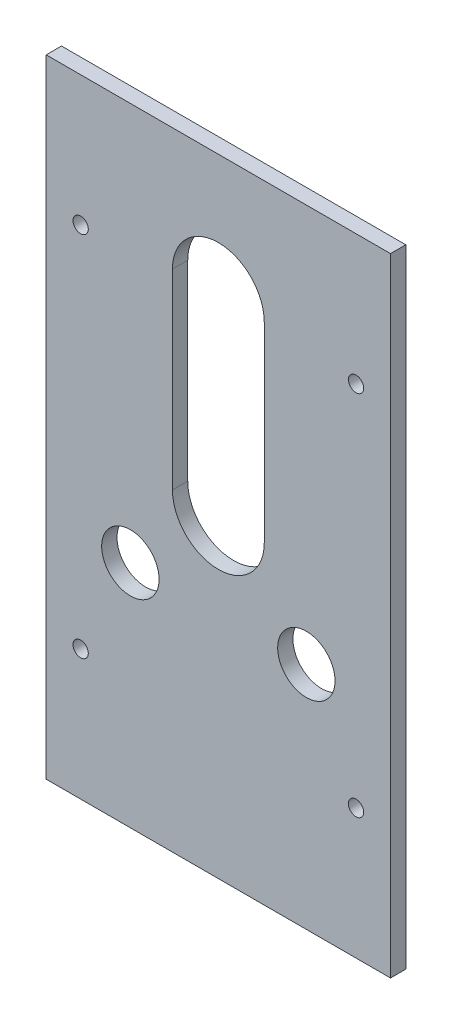
SolidWorks part; units mm, degrees
ref_plane "前视基准面" through (0, 0, 0) normal (0, 0, 1) x (1, 0, 0)
ref_plane "上视基准面" through (0, 0, 0) normal (0, 1, 0) x (1, 0, 0)
ref_plane "右视基准面" through (0, 0, 0) normal (1, 0, 0) x (0, 0, -1)
sketch "草图1" plane through (0, 0, 0) normal (0, 0, 1) x (1, 0, 0)
  line L0 (0, 0) -> (0, 89.6329) construction
  line L1 (-45, -82) -> (45, -82)
  line L2 (-45, -82) -> (-45, 82)
  line L3 (-45, 82) -> (45, 82)
  line L4 (45, -82) -> (45, 82)
  line L5 (-45, -82) -> (45, 82) construction
  line L6 (-45, 82) -> (45, -82) construction
  line L7 (0, 0) -> (0, 50) construction
  line L8 (-12, 0) -> (-12, 50)
  line L9 (12, 0) -> (12, 50)
  circle A0 centre (-36, 48) radius 2
  circle A1 centre (-36, -48) radius 2
  circle A2 centre (36, -48) radius 2
  circle A3 centre (36, 48) radius 2
  arc A4 (-12, 0) -> (12, 0) centre (0, 0) ccw
  arc A5 (12, 50) -> (-12, 50) centre (0, 50) ccw
  circle A6 centre (-23, -22) radius 7.5
  circle A7 centre (23, -22) radius 7.5
  point P0 (0, 0)
  point P18 (0, 25)
  point P27 (-31.7758, -82)
  point P28 (-25.2994, -37.8472)
  dimension "D3" = 4
  dimension "D4" = 4
  dimension "D8" = 25
  dimension "D10" = 12
  dimension "D11" = 15
  dimension "D1" = 90
  dimension "D2" = 164
  dimension "D5" = 9
  dimension "D6" = 34
  dimension "D7" = 34
  dimension "D9" = 25
  dimension "D12" = 22
  dimension "D13" = 60
extrude "凸台-拉伸1" add sketch "草图1" along normal blind 4
